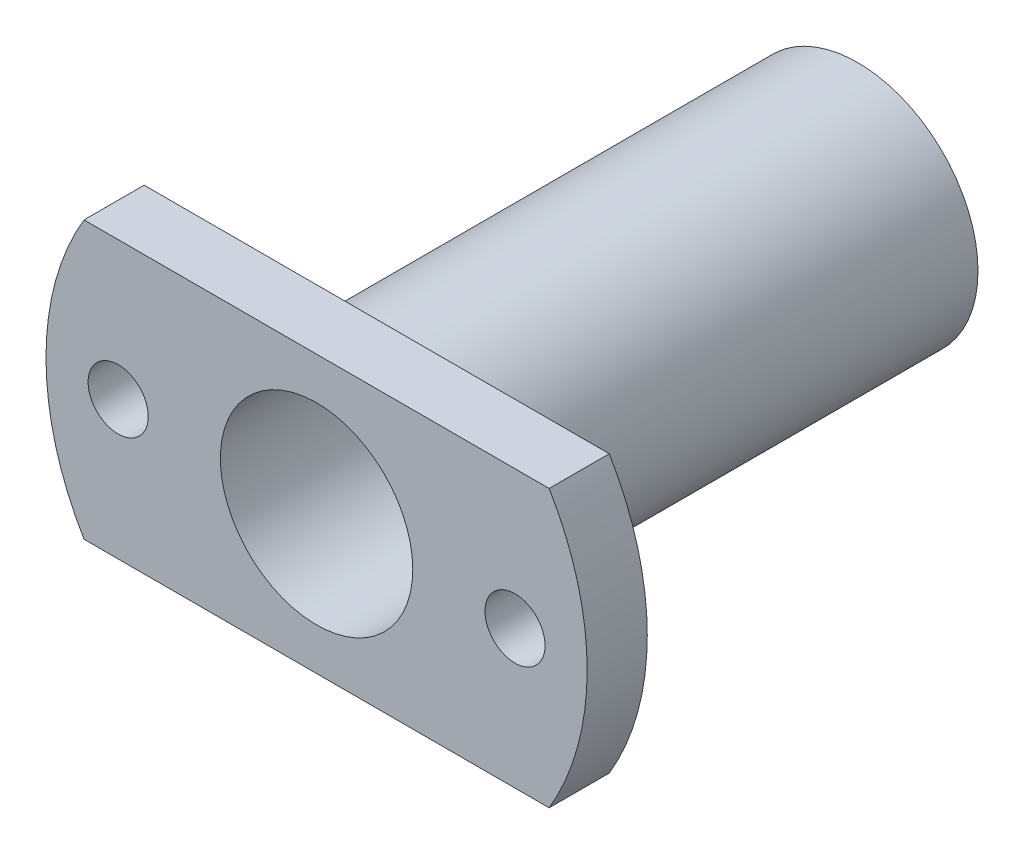
SolidWorks part; units mm, degrees
material "Copper"
ref_plane "Front Plane" through (0, 0, 0) normal (0, 0, 1) x (1, 0, 0)
ref_plane "Top Plane" through (0, 0, 0) normal (0, 1, 0) x (1, 0, 0)
ref_plane "Right Plane" through (0, 0, 0) normal (1, 0, 0) x (0, 0, -1)
sketch "Sketch1" plane through (0, 0, 0) normal (0, 0, 1) x (1, 0, 0)
  line L0 (-30.0768, 0) -> (28.9163, 0) construction
  line L1 (0, 30.9472) -> (0, -28.6261) construction
  line L2 (-19.3391, -11.5) -> (19.3391, -11.5)
  line L3 (-19.3391, 11.5) -> (19.3391, 11.5)
  line L4 (-30.0768, 11.5) -> (28.9163, 11.5) construction
  line L5 (-30.0768, -11.5) -> (28.9163, -11.5) construction
  line L6 (-16.5, 30.9472) -> (-16.5, -28.6261) construction
  line L7 (16.5, 30.9472) -> (16.5, -28.6261) construction
  arc A0 (19.3391, -11.5) -> (19.3391, 11.5) centre (0, 0) ccw
  arc A1 (-19.3391, 11.5) -> (-19.3391, -11.5) centre (0, 0) ccw
  circle A2 centre (-16.5, 0) radius 2.5
  circle A3 centre (16.5, 0) radius 2.5
  dimension "D1" = 45
  dimension "D6" = 5
  dimension "D7" = 5
  dimension "D2" = 11.5
  dimension "D3" = 11.5
  dimension "D4" = 16.5
  dimension "D5" = 16.5
extrude "Boss-Extrude1" add sketch "Sketch1" along normal blind 5
sketch "Sketch2" plane through (0, 0, 0) normal (0, 0, -1) x (-1, 0, 0)
  circle A0 centre (0, 0) radius 10
  dimension "D1" = 20
extrude "Boss-Extrude2" add sketch "Sketch2" along normal blind 40
sketch "Sketch3" plane through (0, 0, 5) normal (0, 0, 1) x (1, 0, 0)
  circle A0 centre (0, 0) radius 8
  dimension "D1" = 16
extrude "Cut-Extrude1" cut sketch "Sketch3" against normal up to next
